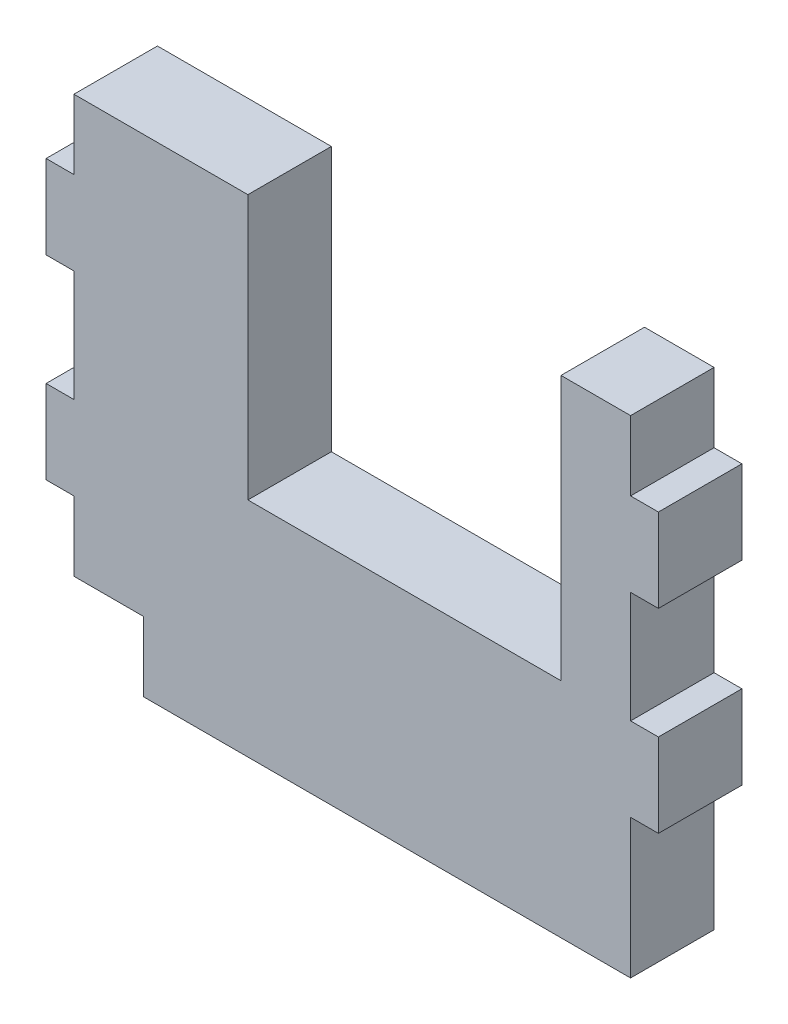
SolidWorks part; units mm, degrees
ref_plane "Спереди" through (0, 0, 0) normal (0, 0, 1) x (1, 0, 0)
ref_plane "Сверху" through (0, 0, 0) normal (0, 1, 0) x (1, 0, 0)
ref_plane "Справа" through (0, 0, 0) normal (1, 0, 0) x (0, 0, -1)
sketch "Эскиз2" plane through (0, 0, 0) normal (0, 0, 1) x (1, 0, 0)
  line L0 (35, 35) -> (40, 35)
  line L1 (5, 0) -> (40, 0)
  line L2 (0, 5) -> (0, 10)
  line L3 (0, 35) -> (12.5, 35)
  line L4 (40, 0) -> (40, 10)
  line L6 (12.5, 35) -> (12.5, 16)
  line L7 (12.5, 16) -> (35, 16)
  line L8 (35, 35) -> (35, 16)
  line L9 (0, 30) -> (0, 35)
  line L10 (-2, 30) -> (0, 30)
  line L11 (-2, 30) -> (-2, 24)
  line L12 (-2, 24) -> (0, 24)
  line L14 (-2, 16) -> (0, 16)
  line L15 (-2, 16) -> (-2, 10)
  line L16 (-2, 10) -> (0, 10)
  line L18 (40, 30) -> (42, 30)
  line L20 (40, 24) -> (42, 24)
  line L21 (42, 30) -> (42, 24)
  line L22 (40, 16) -> (42, 16)
  line L24 (40, 10) -> (42, 10)
  line L25 (42, 16) -> (42, 10)
  line L26 (0, 16) -> (0, 24)
  line L27 (40, 30) -> (40, 35)
  line L28 (40, 16) -> (40, 24)
  line L29 (0, 10) -> (40, 10) construction
  line L32 (0, 5) -> (5, 5)
  line L33 (5, 0) -> (5, 5)
  dimension "D2" = 35
  dimension "D3" = 22.5
  dimension "D4" = 19
  dimension "D5" = 2
  dimension "D6" = 2
  dimension "D7" = 6
  dimension "D8" = 6
  dimension "D9" = 10
  dimension "D10" = 8
  dimension "D11" = 5
  dimension "D12" = 5
  dimension "D13" = 35
  dimension "D14" = 5
extrude "Бобышка-Вытянуть1" add sketch "Эскиз2" along normal blind 6
